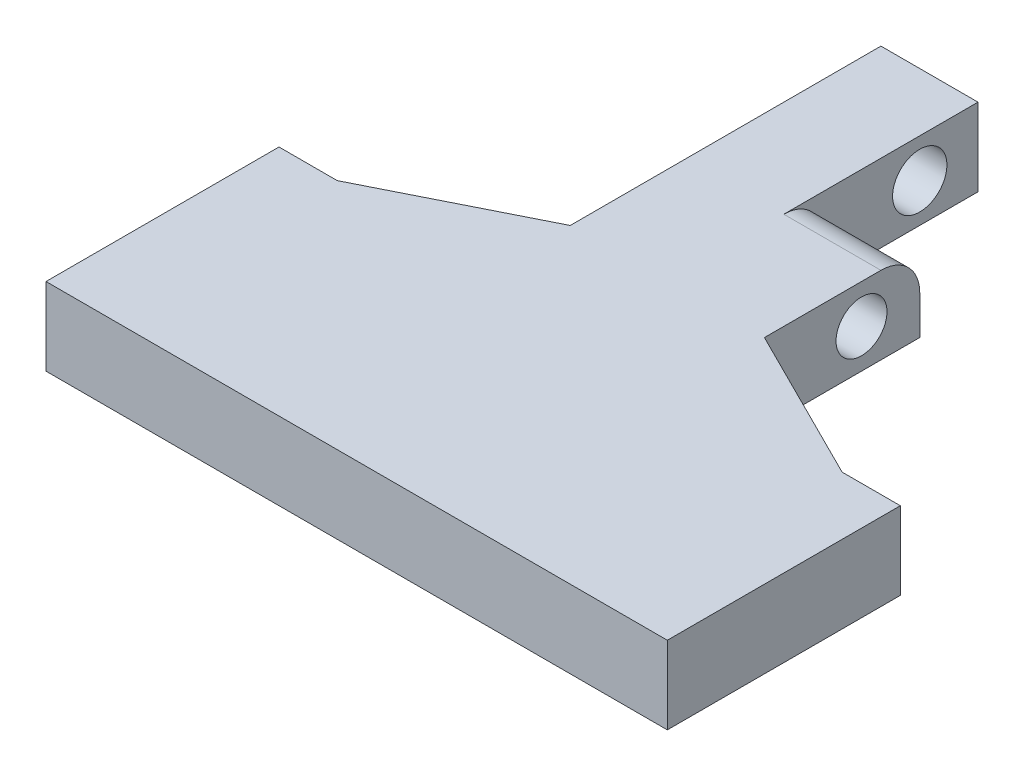
SolidWorks part; units mm, degrees
material "ABS"
ref_plane "Front Plane" through (0, 0, 0) normal (0, 0, 1) x (1, 0, 0)
ref_plane "Top Plane" through (0, 0, 0) normal (0, 1, 0) x (1, 0, 0)
ref_plane "Right Plane" through (0, 0, 0) normal (1, 0, 0) x (0, 0, -1)
sketch "Sketch3" plane through (0, 0, 0) normal (0, 1, 0) x (1, 0, 0)
  line L0 (47.3673, 39.1296) -> (47.3673, -11.6704) construction
  line L1 (21.9673, 7.3796) -> (72.7673, 7.3796)
  line L2 (21.9673, 7.3796) -> (21.9673, -11.6704)
  line L3 (21.9673, -11.6704) -> (72.7673, -11.6704)
  line L4 (72.7673, 7.3796) -> (72.7673, -11.6704)
  line L5 (55.3048, 7.3796) -> (39.4298, 7.3796)
  line L6 (55.3048, 7.3796) -> (55.3048, 39.1296)
  line L7 (55.3048, 39.1296) -> (39.4298, 39.1296)
  line L8 (39.4298, 7.3796) -> (39.4298, 39.1296)
  line L9 (68.0048, 7.3796) -> (55.3048, 13.7296)
  line L10 (26.7298, 7.3796) -> (39.4298, 13.7296)
  dimension "D1" = 50.8
  dimension "D2" = 19.05
  dimension "D3" = 31.75
  dimension "D4" = 15.875
  dimension "D5" = 12.7
  dimension "D6" = 6.35
extrude "Boss-Extrude1" add sketch "Sketch3" along normal blind 6.35 contours L5 L0 L3 L4 L1 | L10 L1 L8 | L1 L9 L6 | L0 L1 L2 L3 | L7 L0 L5 L6 | L0 L7 L8 L1
sketch "Sketch4" plane through (55.3048, 0, 0) normal (1, 0, 0) x (0, 0, -1)
  line L0 (13.7296, 0) -> (39.1296, 0) construction
  line L1 (13.7296, 6.35) -> (13.7296, 0) construction
  line L2 (39.1296, 6.35) -> (39.1296, 0) construction
  circle A0 centre (21.6671, 3.175) radius 2.0828
  circle A1 centre (34.3671, 3.175) radius 2.2225
  dimension "D1" = 3.175
  dimension "D3" = 4.445
  dimension "D2" = 7.9375
  dimension "D4" = 3.175
  dimension "D5" = 4.7625
extrude "Cut-Extrude1" cut sketch "Sketch4" against normal blind 50.8 contours A0 | A1
ref_plane "Plane1" through (47.3673, 0, 0) normal (-1, 0, 0) x (0, 0, 1)
sketch "Sketch5" plane through (0, 6.35, 0) normal (0, 1, 0) x (1, 0, 0)
  line L2 (47.3673, 39.1296) -> (55.3048, 39.1296)
  line L3 (47.3673, 39.1296) -> (47.3673, 26.4296)
  line L4 (47.3673, 26.4296) -> (55.3048, 26.4296)
  line L5 (55.3048, 39.1296) -> (55.3048, 26.4296)
  line L10 (72.7673, 7.3796) -> (68.0048, 7.3796)
  line L11 (68.0048, 7.3796) -> (55.3048, 13.7296)
  line L12 (55.3048, 13.7296) -> (55.3048, 39.1296)
  line L13 (55.3048, 39.1296) -> (39.4298, 39.1296)
  line L14 (39.4298, 39.1296) -> (39.4298, 13.7296)
  line L15 (39.4298, 13.7296) -> (26.7298, 7.3796)
  line L16 (26.7298, 7.3796) -> (21.9673, 7.3796)
  line L17 (21.9673, 7.3796) -> (21.9673, -11.6704)
  line L18 (21.9673, -11.6704) -> (72.7673, -11.6704)
  line L19 (72.7673, -11.6704) -> (72.7673, 7.3796)
  line L20 (72.7673, 7.3796) -> (68.0048, 7.3796)
  line L21 (68.0048, 7.3796) -> (55.3048, 13.7296)
  line L22 (55.3048, 13.7296) -> (55.3048, 39.1296)
  line L23 (55.3048, 39.1296) -> (39.4298, 39.1296)
  line L24 (39.4298, 39.1296) -> (39.4298, 13.7296)
  line L25 (39.4298, 13.7296) -> (26.7298, 7.3796)
  line L26 (26.7298, 7.3796) -> (21.9673, 7.3796)
  line L27 (21.9673, 7.3796) -> (21.9673, -11.6704)
  line L28 (21.9673, -11.6704) -> (72.7673, -11.6704)
  line L29 (72.7673, -11.6704) -> (72.7673, 7.3796)
  line M14 (55.3048, 13.7296) -> (55.3048, 39.1296)
  line M15 (55.3048, 39.1296) -> (39.4298, 39.1296)
  dimension "D2" = 12.7
  dimension "D1" = 0
extrude "Cut-Extrude2" cut sketch "Sketch5" against normal blind 6.35 contours L3 L4 M14 M15
fillet "Fillet1" radius 3.175 1 edges at (51.3361, 6.35, -26.4296)
